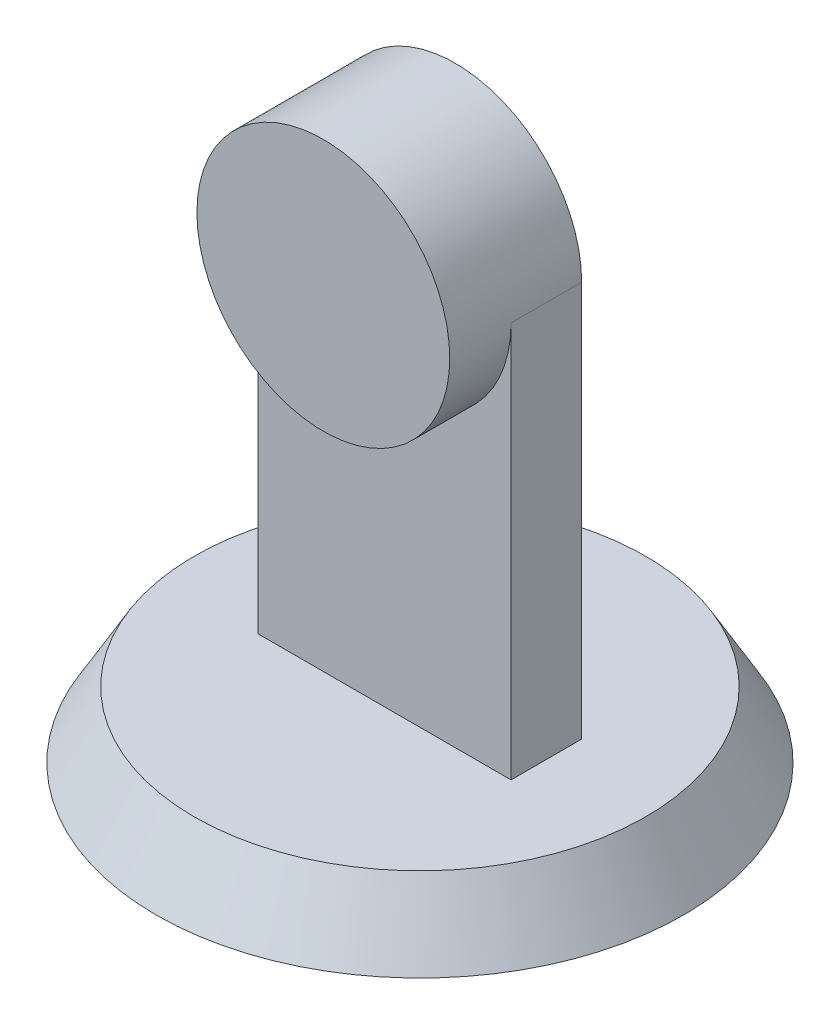
SolidWorks part; units mm, degrees
ref_plane "Front Plane" through (0, 0, 0) normal (0, 0, 1) x (1, 0, 0)
ref_plane "Top Plane" through (0, 0, 0) normal (0, 1, 0) x (1, 0, 0)
ref_plane "Right Plane" through (0, 0, 0) normal (1, 0, 0) x (0, 0, -1)
sketch "Sketch1" plane through (0, 0, 0) normal (0, 1, 0) x (1, 0, 0)
  circle A0 centre (0, 0) radius 40
extrude "Boss-Extrude1" add sketch "Sketch1" along normal blind 10 draft 30
sketch "Sketch2" plane through (0, 10, 0) normal (0, 1, 0) x (1, 0, 0)
  line L1 (-19.1679, 5.3542) -> (19.1679, 5.3542)
  line L2 (-19.1679, 5.3542) -> (-19.1679, -5.3542)
  line L3 (-19.1679, -5.3542) -> (19.1679, -5.3542)
  line L4 (19.1679, 5.3542) -> (19.1679, -5.3542)
  line L5 (-19.1679, 5.3542) -> (19.1679, -5.3542) construction
  line L6 (-19.1679, -5.3542) -> (19.1679, 5.3542) construction
  point P0 (0, 0)
extrude "Boss-Extrude2" add sketch "Sketch2" along normal blind 60
sketch "Sketch3" plane through (0, 0, -5.3542) normal (0, 0, -1) x (-1, 0, 0)
  line L0 (-19.1679, 70) -> (19.1679, 70) construction
  circle A0 centre (0, 70) radius 19.1679
extrude "Boss-Extrude3" add sketch "Sketch3" against normal blind 20
